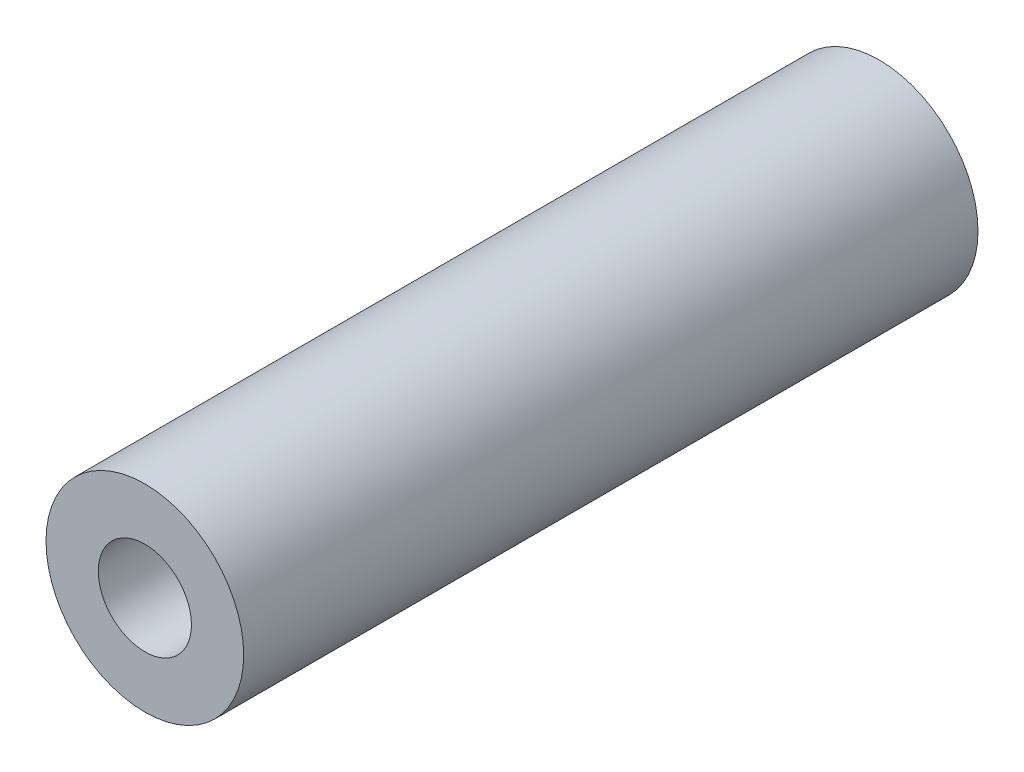
SolidWorks part; units mm, degrees
ref_plane "Front Plane" through (0, 0, 0) normal (0, 0, 1) x (1, 0, 0)
ref_plane "Top Plane" through (0, 0, 0) normal (0, 1, 0) x (1, 0, 0)
ref_plane "Right Plane" through (0, 0, 0) normal (1, 0, 0) x (0, 0, -1)
sketch "S01 - Annular section" plane through (0, 0, 0) normal (0, 0, 1) x (1, 0, 0)
  circle A0 centre (0, 0) radius 7
  circle A1 centre (0, 0) radius 3.3
  dimension "D1" = 6.6
  dimension "D2" = 14
extrude "01 - Annular section" add sketch "S01 - Annular section" along normal blind 52
